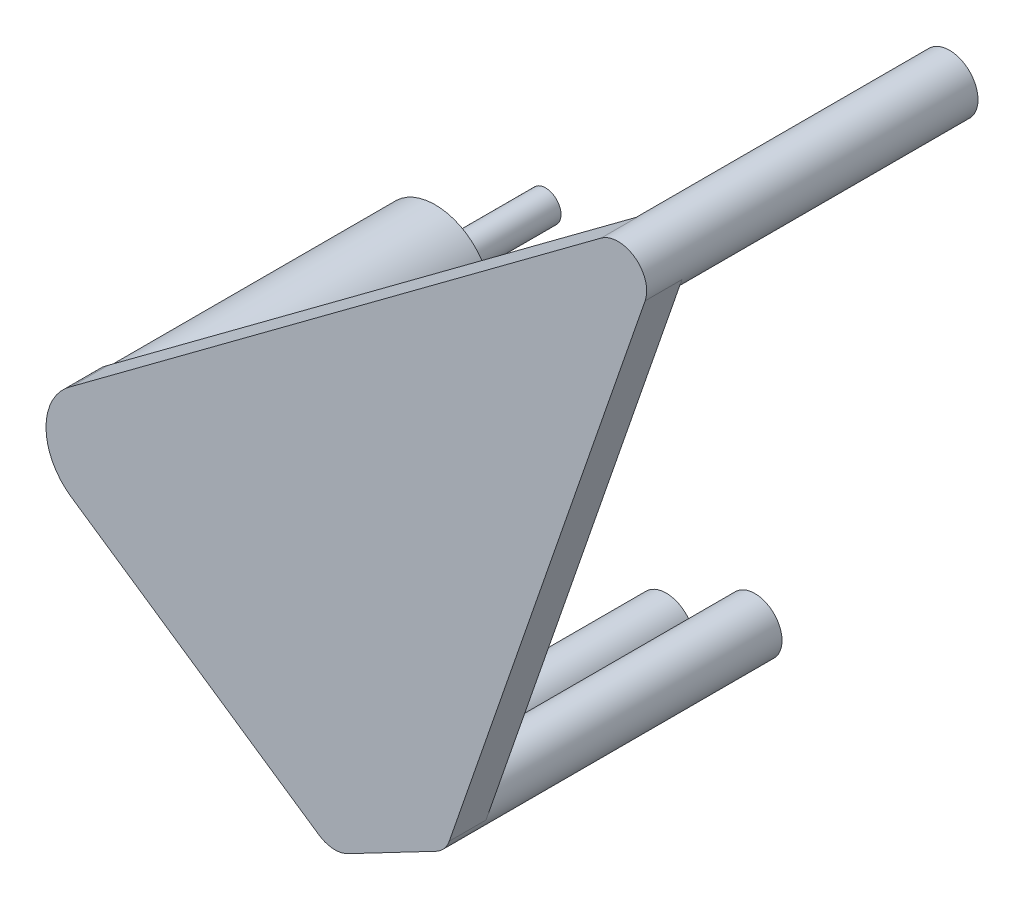
SolidWorks part; units mm, degrees
ref_plane "Front Plane" through (0, 0, 0) normal (0, 0, 1) x (1, 0, 0)
ref_plane "Top Plane" through (0, 0, 0) normal (0, 1, 0) x (1, 0, 0)
ref_plane "Right Plane" through (0, 0, 0) normal (1, 0, 0) x (0, 0, -1)
sketch "Sketch2" plane through (0, 0, 0) normal (0, 0, 1) x (1, 0, 0)
  line L0 (-1395.7664, 232.8715) -> (-1395.7664, 1985.4011) construction
  line L168 (-1647.1874, 301.1556) -> (-1647.1874, 2317.1556) construction
  line L179 (-133.803, 33.5734) -> (-178.7982, 33.5734)
  line L180 (-178.7982, 33.5734) -> (-260.9968, -5.8692)
  line L181 (-260.9968, -5.8692) -> (-257.1598, -33.9699)
  line L182 (-257.1598, -33.9699) -> (-257.1598, -44.8332)
  line L183 (-257.1598, -44.8332) -> (-296.5534, -63.736)
  line L184 (-296.5534, -63.736) -> (-308.6754, -62.5468)
  line L185 (-308.6754, -62.5468) -> (-308.6754, 117.1411)
  line L186 (-308.6754, 117.1411) -> (-300.756, 113.4929)
  line L187 (-300.756, 113.4929) -> (-175.5429, 112.4381)
  line L188 (-175.5429, 112.4381) -> (-168.1865, 115.968)
  line L189 (-168.1865, 115.968) -> (-50.9118, 113.4929)
  line L190 (-50.9118, 113.4929) -> (-50.9118, 115.968)
  line L191 (-50.9118, 115.968) -> (-36.6913, 135.8252)
  line L192 (-36.6913, 135.8252) -> (-31.5738, 138.2808)
  line L193 (-31.5738, 138.2808) -> (-5.8838, 150.608)
  line L194 (-5.8838, 150.608) -> (107.4846, 149.1823)
  line L195 (107.4846, 149.1823) -> (128.3733, 117.1411)
  line L196 (128.3733, 117.1411) -> (145.7874, 117.1411)
  line L197 (145.7874, 117.1411) -> (152.1653, 114.203)
  line L198 (152.1653, 114.203) -> (160.648, 104.4673)
  line L199 (160.648, 104.4673) -> (167.8375, 104.4673)
  line L200 (167.8375, 104.4673) -> (173.3888, 98.9159)
  line L201 (173.3888, 98.9159) -> (173.8274, 95.7036)
  line L202 (173.8274, 95.7036) -> (167.8375, 91.7986)
  line L203 (167.8375, 91.7986) -> (233.2133, 90.9764)
  line L204 (233.2133, 90.9764) -> (240.6201, 87.5643)
  line L205 (240.6201, 87.5643) -> (257.6468, 66.4195)
  line L206 (257.6468, 66.4195) -> (257.6468, 63.8778)
  line L207 (257.6468, 63.8778) -> (249.598, 53.5696)
  line L208 (249.598, 53.5696) -> (248.0214, 45.3458)
  line L209 (248.0214, 45.3458) -> (254.1361, 32.6026)
  line L210 (254.1361, 32.6026) -> (254.7034, 28.4483)
  line L211 (254.7034, 28.4483) -> (250.1892, 27.2972)
  line L212 (250.1892, 27.2972) -> (244.5367, 15.027)
  line L213 (244.5367, 15.027) -> (242.0682, 12.5585)
  line L214 (242.0682, 12.5585) -> (239.1826, 12.5585)
  line L215 (239.1826, 12.5585) -> (239.1826, -0.2727)
  line L216 (239.1826, -0.2727) -> (189.2936, -18.7617)
  line L217 (189.2936, -18.7617) -> (184.6378, -28.8683)
  line L218 (184.6378, -28.8683) -> (165.5344, -32.0319)
  line L219 (165.5344, -32.0319) -> (157.3487, -26.1697)
  line L220 (157.3487, -26.1697) -> (147.9104, -4.5175)
  line L221 (147.9104, -4.5175) -> (132.6552, -4.1955)
  line L222 (132.6552, -4.1955) -> (128.8477, -9.0718)
  line L223 (128.8477, -9.0718) -> (109.604, -9.5172)
  line L224 (109.604, -9.5172) -> (106.7342, -11.6012)
  line L225 (106.7342, -11.6012) -> (21.3384, -11.6012)
  line L226 (21.3384, -11.6012) -> (21.3384, -19.9195)
  line L227 (21.3384, -19.9195) -> (19.8686, -24.822)
  line L228 (19.8686, -24.822) -> (16.8589, -24.822)
  line L229 (16.8589, -24.822) -> (14.5306, -21.6157)
  line L230 (14.5306, -21.6157) -> (13.9192, -13.6231)
  line L231 (13.9192, -13.6231) -> (13.9192, -11.1734)
  line L232 (13.9192, -11.1734) -> (12.3931, -9.0718)
  line L233 (12.3931, -9.0718) -> (-7.8979, -9.5414)
  line L234 (-7.8979, -9.5414) -> (-12.5558, -4.1955)
  line L235 (-12.5558, -4.1955) -> (-14.2294, -5.6537)
  line L236 (-14.2294, -5.6537) -> (-28.9642, -34.3324)
  line L237 (-28.9642, -34.3324) -> (-26.5892, -51.7262)
  line L238 (-26.5892, -51.7262) -> (-44.481, -92.8698)
  line L239 (-44.481, -92.8698) -> (-47.4697, -95.0401)
  line L240 (-47.4697, -95.0401) -> (-52.7041, -95.0401)
  line L241 (-52.7041, -95.0401) -> (-67.0585, -88.798)
  line L242 (-67.0585, -88.798) -> (-69.5077, -87.5395)
  line L243 (-69.5077, -87.5395) -> (-72.2263, -83.3696)
  line L244 (-72.2263, -83.3696) -> (-94.1204, -75.2618)
  line L245 (-94.1204, -75.2618) -> (-95.7689, -76.3365)
  line L246 (-95.7689, -76.3365) -> (-98.8583, -75.7442)
  line L247 (-98.8583, -75.7442) -> (-110.0115, -70.0138)
  line L248 (-110.0115, -70.0138) -> (-111.1609, -67.377)
  line L249 (-111.1609, -67.377) -> (-131.1287, -67.8392)
  line L250 (-131.1287, -67.8392) -> (-135.99, -66.3816)
  line L251 (-135.99, -66.3816) -> (-145.0882, -55.083)
  line L252 (-145.0882, -55.083) -> (-144.4774, -48.858)
  line L253 (-144.4774, -48.858) -> (-141.4827, -43.0293)
  line L254 (-141.4827, -43.0293) -> (-142.9801, -39.5942)
  line L255 (-142.9801, -39.5942) -> (-142.9801, -34.3324)
  line L256 (-142.9801, -34.3324) -> (-142.3227, -27.6314)
  line L257 (-142.3227, -27.6314) -> (-141.8897, -23.2189)
  line L258 (-141.8897, -23.2189) -> (-138.5197, -15.9033)
  line L259 (-138.5197, -15.9033) -> (-134.3792, -9.0718)
  line L260 (-134.3792, -9.0718) -> (-129.3025, -2.5702)
  line L261 (-129.3025, -2.5702) -> (-125.2312, 0.9771)
  line L262 (-125.2312, 0.9771) -> (-121.8226, 3.1993)
  line L263 (-121.8226, 3.1993) -> (-120.8136, 4.4558)
  line L264 (-120.8136, 4.4558) -> (-119.6766, 5.8716)
  line L265 (-119.6766, 5.8716) -> (-118.9997, 7.3526)
  line L266 (-118.9997, 7.3526) -> (-118.2822, 9.153)
  line L267 (-118.2822, 9.153) -> (-118.0908, 11.3455)
  line L268 (-118.0908, 11.3455) -> (-117.7885, 14.807)
  line L269 (-117.7885, 14.807) -> (-117.7885, 18.2254)
  line L270 (-117.7885, 18.2254) -> (-117.9396, 19.8564)
  line L271 (-117.9396, 19.8564) -> (-118.6819, 22.0613)
  line L272 (-118.6819, 22.0613) -> (-118.9087, 22.7352)
  line L273 (-120.8136, 24.9682) -> (-118.9087, 22.7352)
  line L274 (-120.8136, 24.9682) -> (-123.5044, 27.659)
  line L275 (-123.5044, 27.659) -> (-128.0489, 30.1279)
  line L276 (-128.0489, 30.1279) -> (-132.0963, 32.3267)
  line L277 (-132.0963, 32.3267) -> (-133.803, 33.5734)
  line L278 (-12.5558, 106.4159) -> (-12.5558, 127.7793)
  line L279 (-12.5558, 127.7793) -> (-10.3407, 130.812)
  line L280 (-10.3407, 130.812) -> (-2.8432, 132.6568)
  line L281 (-2.8432, 132.6568) -> (3.2533, 133.4505)
  line L282 (3.2533, 133.4505) -> (8.705, 132.4078)
  line L283 (8.705, 132.4078) -> (13.5161, 130.3225)
  line L284 (13.5161, 130.3225) -> (14.5306, 129.7875)
  line L285 (14.5306, 129.7875) -> (18.1825, 129.5615)
  line L286 (18.1825, 129.5615) -> (22.2841, 131.0736)
  line L287 (22.2841, 131.0736) -> (24.7526, 131.7344)
  line L288 (24.7526, 131.7344) -> (27.9259, 132.1475)
  line L289 (27.9259, 132.1475) -> (29.9862, 131.9409)
  line L290 (29.9862, 131.9409) -> (33.3385, 131.1803)
  line L291 (33.3385, 131.1803) -> (37.6837, 128.8886)
  line L292 (37.6837, 128.8886) -> (40.3887, 128.8886)
  line L293 (40.3887, 128.8886) -> (41.2282, 128.8886)
  line L294 (41.2282, 128.8886) -> (42.5759, 129.7875)
  line L295 (42.5759, 129.7875) -> (45.9586, 131.1803)
  line L296 (45.9586, 131.1803) -> (49.4, 131.5606)
  line L297 (49.4, 131.5606) -> (54.1505, 131.5606)
  line L298 (54.1505, 131.5606) -> (60.6434, 128.5787)
  line L299 (60.6434, 128.5787) -> (63.484, 128.2939)
  line L300 (63.484, 128.2939) -> (67.3904, 130.0697)
  line L301 (67.3904, 130.0697) -> (71.1014, 130.9828)
  line L302 (71.1014, 130.9828) -> (76.1342, 131.539)
  line L303 (76.1342, 131.539) -> (79.4118, 131.7344)
  line L304 (79.4118, 131.7344) -> (85.6851, 129.7875)
  line L305 (85.6851, 129.7875) -> (91.3626, 126.7931)
  line L306 (91.3626, 126.7931) -> (96.0039, 114.203)
  line L307 (96.0039, 114.203) -> (96.5933, 108.8694)
  line L308 (96.5933, 108.8694) -> (89.9928, 104.4673)
  line L309 (89.9928, 104.4673) -> (76.5787, 104.4673)
  line L310 (76.5787, 104.4673) -> (71.5086, 102.1625)
  line L311 (71.5086, 102.1625) -> (69.7451, 106.9465)
  line L312 (69.7451, 106.9465) -> (-8.9538, 110.8324)
  line L313 (-8.9538, 110.8324) -> (-12.5558, 106.4159)
  line L314 (-60.9482, -11.1734) -> (-49.9855, -15.9033)
  line L315 (-49.9855, -15.9033) -> (-46.7509, -18.5414)
  line L316 (-46.7509, -18.5414) -> (-46.2015, -19.8276)
  line L317 (-46.2015, -19.8276) -> (-45.64, -22.1577)
  line L318 (-45.64, -22.1577) -> (-45.3873, -24.822)
  line L319 (-45.3873, -24.822) -> (-45.7804, -27.267)
  line L320 (-45.7804, -27.267) -> (-46.7509, -29.0918)
  line L321 (-46.7509, -29.0918) -> (-48.5488, -31.2962)
  line L322 (-48.5488, -31.2962) -> (-50.9118, -32.9458)
  line L323 (-50.9118, -32.9458) -> (-53.2361, -33.5935)
  line L324 (-53.2361, -33.5935) -> (-54.2647, -34.0329)
  line L325 (-54.2647, -34.0329) -> (-55.4669, -35.2182)
  line L326 (-55.4669, -35.2182) -> (-57.0208, -38.1397)
  line L327 (-57.0208, -38.1397) -> (-57.0208, -40.6689)
  line L328 (-57.0208, -40.6689) -> (-56.1372, -41.7577)
  line L329 (-56.1372, -41.7577) -> (-55.3169, -42.7683)
  line L330 (-55.3169, -42.7683) -> (-54.5882, -44.4739)
  line L331 (-54.5882, -44.4739) -> (-54.4752, -47.7702)
  line L332 (-54.4752, -47.7702) -> (-55.2128, -50.7833)
  line L333 (-55.2128, -50.7833) -> (-57.3319, -54.2224)
  line L334 (-57.3319, -54.2224) -> (-59.8885, -59.0289)
  line L335 (-59.8885, -59.0289) -> (-61.4713, -62.0047)
  line L336 (-61.4713, -62.0047) -> (-63.4405, -64.2241)
  line L337 (-63.4405, -64.2241) -> (-67.2393, -66.8762)
  line L338 (-67.2393, -66.8762) -> (-70.4172, -68.6919)
  line L339 (-70.4172, -68.6919) -> (-78.8872, -66.3816)
  line L340 (-78.8872, -66.3816) -> (-86.5217, -64.0024)
  line L341 (-86.5217, -64.0024) -> (-88.6105, -59.6115)
  line L342 (-88.6105, -59.6115) -> (-88.6105, -57.485)
  line L343 (-88.6105, -57.485) -> (-90.1039, -56.16)
  line L344 (-90.1039, -56.16) -> (-90.1039, -54.5542)
  line L345 (-90.1039, -54.5542) -> (-82.6486, -24.0985)
  line L346 (-119.8921, 4.8168) -> (-73.8388, -14.1836) construction
  line L347 (-82.6486, -24.0985) -> (-78.2974, -19.9195)
  line L348 (-78.2974, -19.9195) -> (-76.1757, -21.0481)
  line L349 (-76.1757, -21.0481) -> (-75.3081, -23.8876)
  line L350 (-75.3081, -23.8876) -> (-69.5998, -26.0704)
  line L351 (-69.5998, -26.0704) -> (-66.4787, -23.5373)
  line L352 (-66.4787, -23.5373) -> (-71.3875, -17.4893)
  line L353 (-71.3875, -17.4893) -> (-68.8849, -13.428)
  line L354 (-68.8849, -13.428) -> (-67.0585, -13.1313)
  line L355 (-67.0585, -13.1313) -> (-62.6304, -10.8786)
  line L356 (-62.6304, -10.8786) -> (-60.9482, -11.1734)
  circle A0 centre (-135.99, 14.807) radius 14.5
  circle A1 centre (-53.2361, -23.5373) radius 7.0481
  circle A2 centre (-2.8432, 123.138) radius 7.405
  circle A3 centre (-76.1757, -35.2182) radius 7.3431
  dimension "D1" = 29
extrude "Boss-Extrude5" add sketch "Sketch2" along normal mid plane 81.026 contours A0 | A3 | A1 | A2
sketch "Sketch6" plane through (0, 0, 40.513) normal (0, 0, 1) x (1, 0, 0)
  line L0 (-80.3108, -41.2863) -> (-144.4368, 2.4113)
  line L1 (-144.4368, 27.2026) -> (-7.2583, 129.0829)
  line L2 (-72.7689, -41.7232) -> (-49.9662, -29.7809)
  line L3 (-46.5758, -25.8427) -> (4.1545, 120.7158)
  arc A0 (-144.4368, 27.2026) -> (-144.4368, 2.4113) centre (-135.99, 14.807) ccw
  circle A1 centre (-76.1757, -35.2182) radius 7.3431
  circle A2 centre (-53.2361, -23.5373) radius 7.0481
  circle A3 centre (-2.8432, 123.138) radius 7.405
  circle M1 centre (-135.99, 14.807) radius 14.5
extrude "Boss-Extrude6" add sketch "Sketch6" along normal mid plane 9.525 contours A3 L1 L0 A1 L2 A2 L3 M1 | M1 | A1 | A2 | A3 L2
ref_plane "Plane1" through (-46.5758, -25.8427, 35.7505) normal (0.3271, 0.945, 0) x (0.945, -0.3271, 0)
sketch "Sketch9" plane through (0, 0, -40.513) normal (0, 0, -1) x (-1, 0, 0)
  circle A0 centre (53.2361, -23.5373) radius 1.27
  circle A1 centre (76.1757, -35.2182) radius 1.27
  circle A3 centre (2.8432, 123.138) radius 1.27
  dimension "D1" = 2.54
  dimension "D3" = 2.54
  dimension "D4" = 2.54
extrude "Cut-Extrude2" cut sketch "Sketch9" against normal blind 9.525
sketch "Sketch10" plane through (0, 0, -40.513) normal (0, 0, -1) x (-1, 0, 0)
  circle A0 centre (135.99, 14.807) radius 4
  dimension "D1" = 8
extrude "Boss-Extrude7" add sketch "Sketch10" along normal blind 28.575
